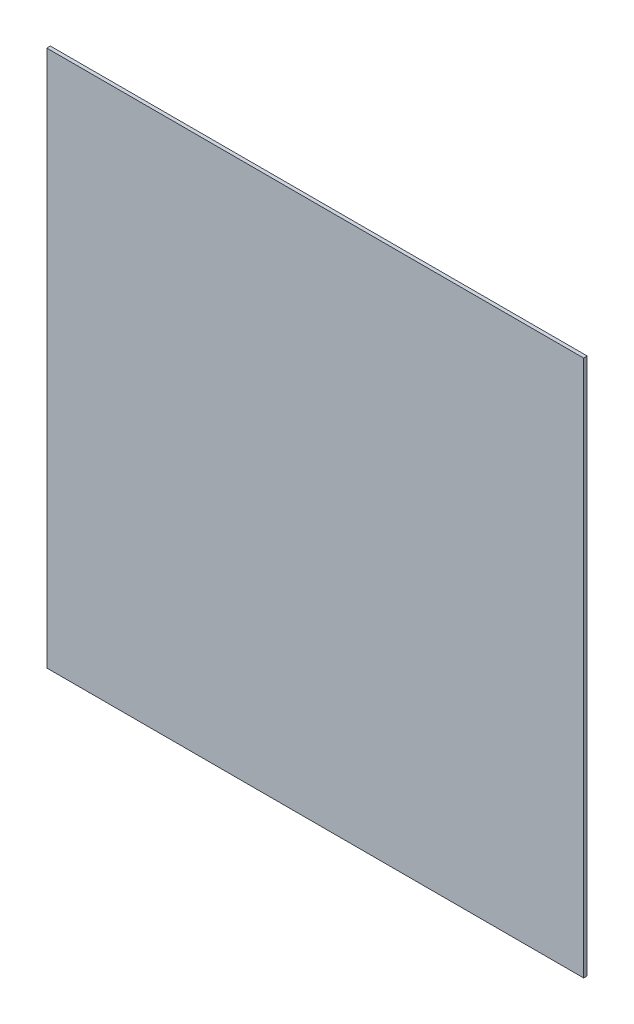
SolidWorks part; units mm, degrees
material "Perspex (TM) GS Acrylic Cast Sheet"
ref_plane "Front Plane" through (0, 0, 0) normal (0, 0, 1) x (1, 0, 0)
ref_plane "Top Plane" through (0, 0, 0) normal (0, 1, 0) x (1, 0, 0)
ref_plane "Right Plane" through (0, 0, 0) normal (1, 0, 0) x (0, 0, -1)
sketch "Sketch1" plane through (0, 0, 0) normal (0, 0, 1) x (1, 0, 0)
  line L1 (0, 0) -> (450, 0)
  line L2 (0, 0) -> (0, 450)
  line L3 (0, 450) -> (450, 450)
  line L4 (450, 0) -> (450, 450)
  dimension "D1" = 450
  dimension "D2" = 450
extrude "Boss-Extrude1" add sketch "Sketch1" along normal blind 3
